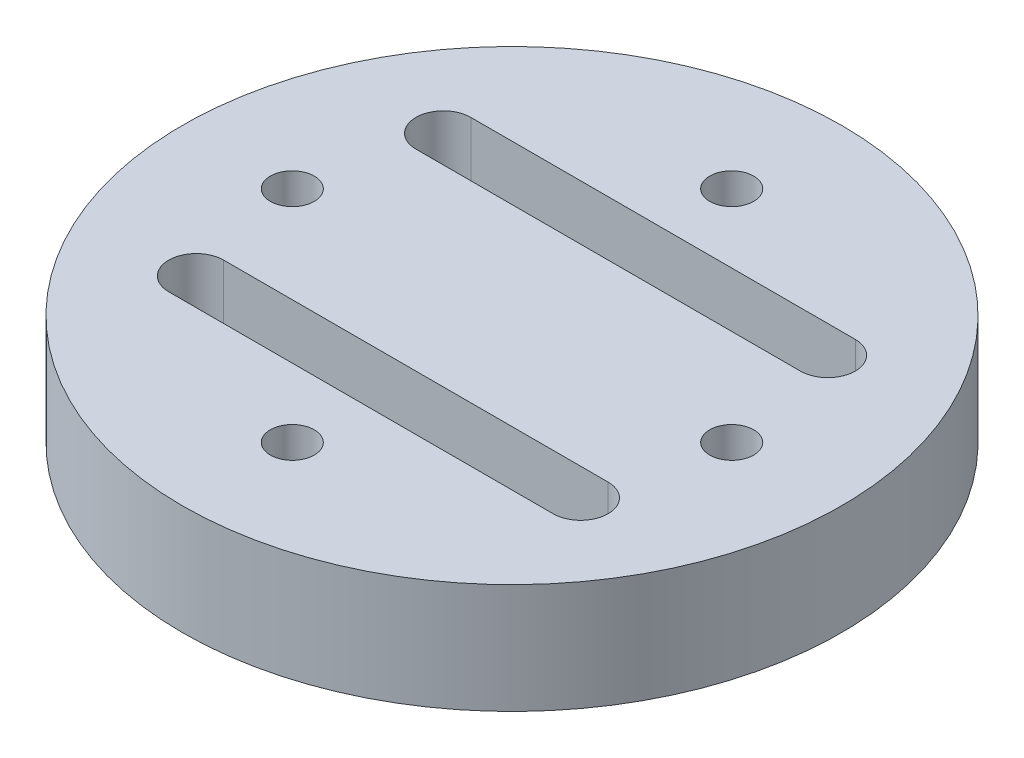
SolidWorks part; units mm, degrees
ref_plane "Front Plane" through (0, 0, 0) normal (0, 0, 1) x (1, 0, 0)
ref_plane "Top Plane" through (0, 0, 0) normal (0, 1, 0) x (1, 0, 0)
ref_plane "Right Plane" through (0, 0, 0) normal (1, 0, 0) x (0, 0, -1)
sketch "Sketch2" plane through (0, 0, 0) normal (0, 1, 0) x (1, 0, 0)
  circle A0 centre (0, 0) radius 60
  dimension "D1" = 120
extrude "Boss-Extrude1" add sketch "Sketch2" along normal blind 20
sketch "Sketch3" plane through (0, 0, 0) normal (0, -1, 0) x (1, 0, 0)
  line L1 (-30, 12.5) -> (30, 12.5)
  line L2 (-30, 12.5) -> (-30, -12.5)
  line L3 (-30, -12.5) -> (30, -12.5)
  line L4 (30, 12.5) -> (30, -12.5)
  line L5 (-30, 12.5) -> (30, -12.5) construction
  line L6 (-30, -12.5) -> (30, 12.5) construction
  point P0 (0, 0)
  dimension "D1" = 25
  dimension "D2" = 60
extrude "Cut-Extrude1" cut sketch "Sketch3" against normal blind 8
sketch "Sketch4" plane through (0, 0, -12.5) normal (0, 0, 1) x (1, 0, 0)
  line L0 (-60, 0) -> (60, 0) construction
  line L1 (0, -10.0055) -> (0, 27.6475) construction
  circle A0 centre (-17.5, 0) radius 6
  circle A1 centre (17.5, 0) radius 6
  dimension "D1" = 12
  dimension "D2" = 35
extrude "Cut-Extrude2" cut sketch "Sketch4" against normal blind 17 and the other way blind 40
sketch "Sketch5" plane through (0, 0, 0) normal (0, 0, 1) x (1, 0, 0)
  line L0 (-60, 0) -> (60, 0) construction
  line L1 (0, -7.139) -> (0, 30.1134) construction
  circle A0 centre (-17.5, 0) radius 16
  circle A1 centre (17.5, 0) radius 16
  dimension "D1" = 32
  dimension "D2" = 35
extrude "Cut-Extrude3" cut sketch "Sketch5" against normal mid plane 32.5
sketch "Sketch6" plane through (0, 20, 0) normal (0, 1, 0) x (1, 0, 0)
  circle A0 centre (0, 40) radius 4
  circle A1 centre (40, 0) radius 4
  circle A2 centre (0, -40) radius 4
  circle A3 centre (-40, 0) radius 4
  point P2 (0, 0)
  point P4 (-6.5661, 0)
  point P5 (0, 0)
  point P12 (0, 0)
  dimension "D2" = 8
  dimension "D1" = 40
  dimension "D3" = 4
extrude "Cut-Extrude4" cut sketch "Sketch6" against normal through all
sketch "Sketch7" plane through (0, 20, 0) normal (0, 1, 0) x (1, 0, 0)
  line L0 (-35, 22.5) -> (35, 22.5) construction
  line L1 (-35, 27.5) -> (35, 27.5)
  line L2 (-35, 17.5) -> (35, 17.5)
  line L3 (-80.0027, 0) -> (88.9879, 0) construction
  line L4 (-35, -22.5) -> (35, -22.5) construction
  line L5 (-35, -27.5) -> (35, -27.5)
  line L6 (-35, -17.5) -> (35, -17.5)
  arc A0 (-35, 27.5) -> (-35, 17.5) centre (-35, 22.5) ccw
  arc A1 (35, 17.5) -> (35, 27.5) centre (35, 22.5) ccw
  arc A2 (-35, -27.5) -> (-35, -17.5) centre (-35, -22.5) cw
  arc A3 (35, -17.5) -> (35, -27.5) centre (35, -22.5) cw
  point P2 (0, 22.5)
  point P10 (0, 0)
  point P11 (0, 0)
  point P14 (0, -22.5)
  dimension "D1" = 10
  dimension "D2" = 27.5
  dimension "D3" = 70
extrude "Cut-Extrude5" cut sketch "Sketch7" against normal through all
